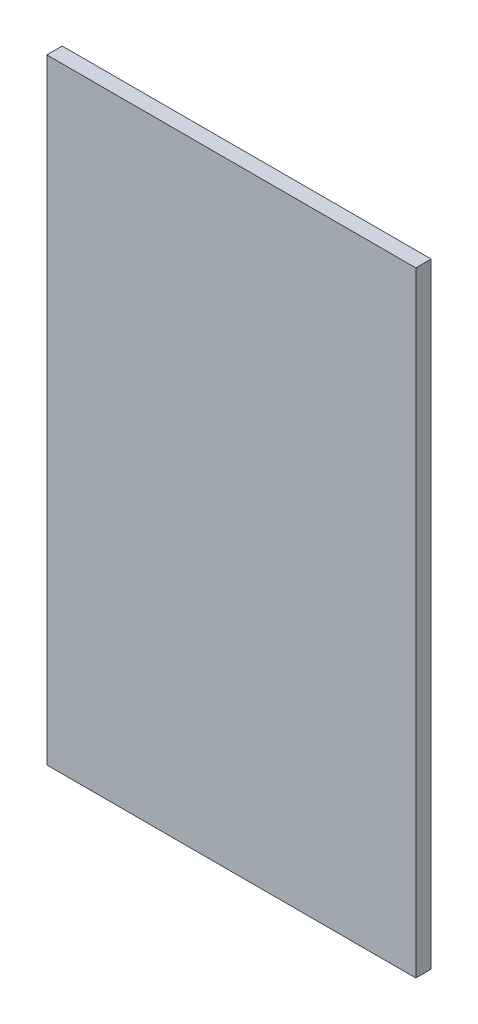
SolidWorks part; units mm, degrees
ref_plane "Front Plane" through (0, 0, 0) normal (0, 0, 1) x (1, 0, 0)
ref_plane "Top Plane" through (0, 0, 0) normal (0, 1, 0) x (1, 0, 0)
ref_plane "Right Plane" through (0, 0, 0) normal (1, 0, 0) x (0, 0, -1)
sketch "Sketch1" plane through (0, 0, 0) normal (0, 0, 1) x (1, 0, 0)
  line L1 (-249.0535, -159.5414) -> (-96.6535, -159.5414)
  line L2 (-249.0535, -159.5414) -> (-249.0535, 94.4586)
  line L3 (-249.0535, 94.4586) -> (-96.6535, 94.4586)
  line L4 (-96.6535, -159.5414) -> (-96.6535, 94.4586)
  dimension "D1" = 254
  dimension "D2" = 152.4
extrude "Boss-Extrude1" add sketch "Sketch1" along normal blind 6.35
